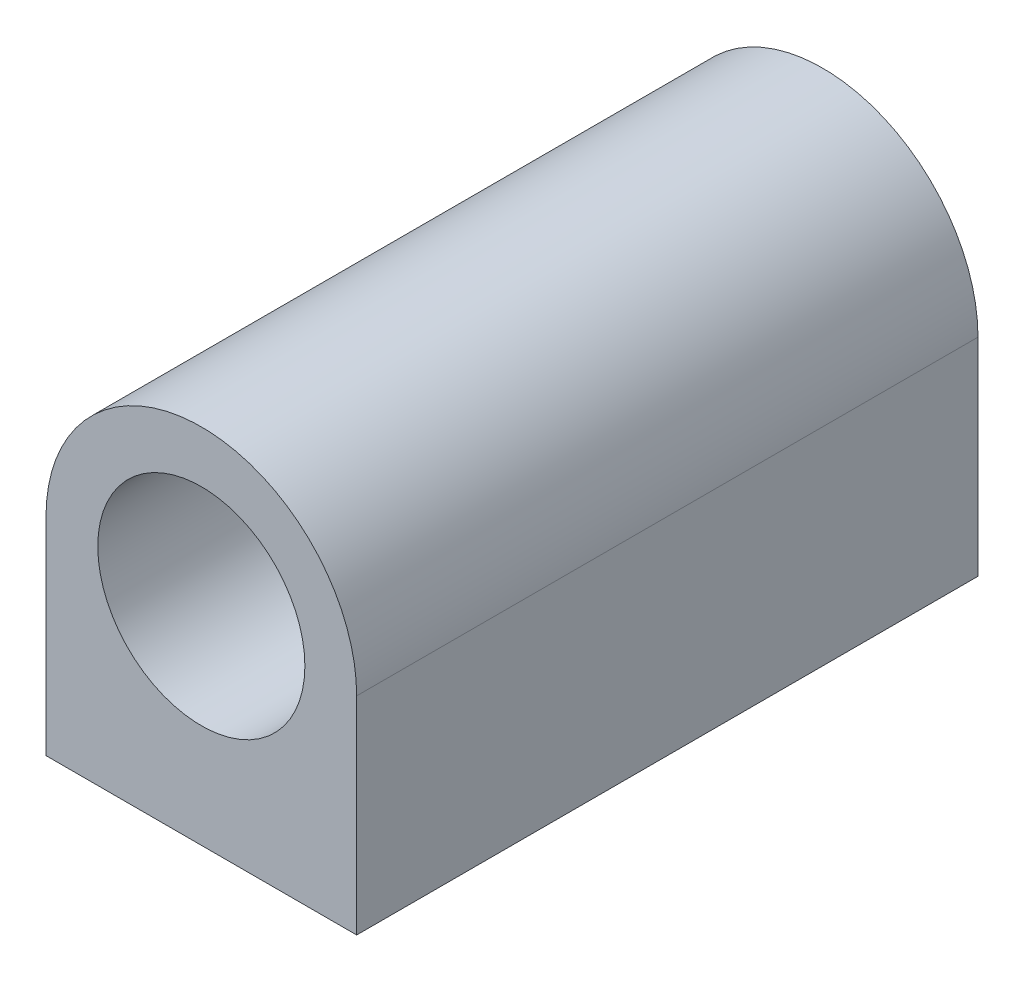
SolidWorks part; units mm, degrees
ref_plane "Front Plane" through (0, 0, 0) normal (0, 0, 1) x (1, 0, 0)
ref_plane "Top Plane" through (0, 0, 0) normal (0, 1, 0) x (1, 0, 0)
ref_plane "Right Plane" through (0, 0, 0) normal (1, 0, 0) x (0, 0, -1)
sketch "Sketch1" plane through (0, 0, 0) normal (0, 0, 1) x (1, 0, 0)
  line L0 (-19.05, 25.4) -> (-19.05, 0)
  line L1 (-19.05, 0) -> (19.05, 0)
  line L2 (19.05, 0) -> (19.05, 25.4)
  arc A0 (19.05, 25.4) -> (-19.05, 25.4) centre (0, 25.4) ccw
  circle A1 centre (0, 25.4) radius 12.7
  dimension "D1" = 38.1
  dimension "D2" = 25.4
  dimension "D3" = 25.4
extrude "Boss-Extrude1" add sketch "Sketch1" along normal mid plane 76.2
hole_wizard "Hole1" positions "Sketch2" profile "Sketch3" legacy
sketch "Sketch2" plane through (0, 0, 0) normal (0, -1, 0) x (-1, 0, 0)
  line L1 (-19.05, -38.1) -> (-19.05, 38.1) construction
  point P0 (-12.7, 31.75)
  point P2 (-12.7, -31.75)
  point P10 (0, 0)
  dimension "D1" = 63.5
  dimension "D2" = 31.75
  dimension "D3" = 6.35
sketch "Sketch3" plane through (12.7, 0, -31.75) normal (1, 0, 0) x (0, 0, -1)
  line L0 (0, 0) -> (0, 12.7)
  line L1 (0, 12.7) -> (1.651, 12.7)
  line L2 (1.651, 12.7) -> (1.651, 0)
  line L3 (1.651, 0) -> (0, 0)
  line L4 (0, 110) -> (0, -10) construction
  dimension "Diameter" = 3.302
  dimension "Depth" = 12.7
pattern_linear "LPattern1" count 2 spacing 25.4 along (-1, 0, 0) of "Hole1"
